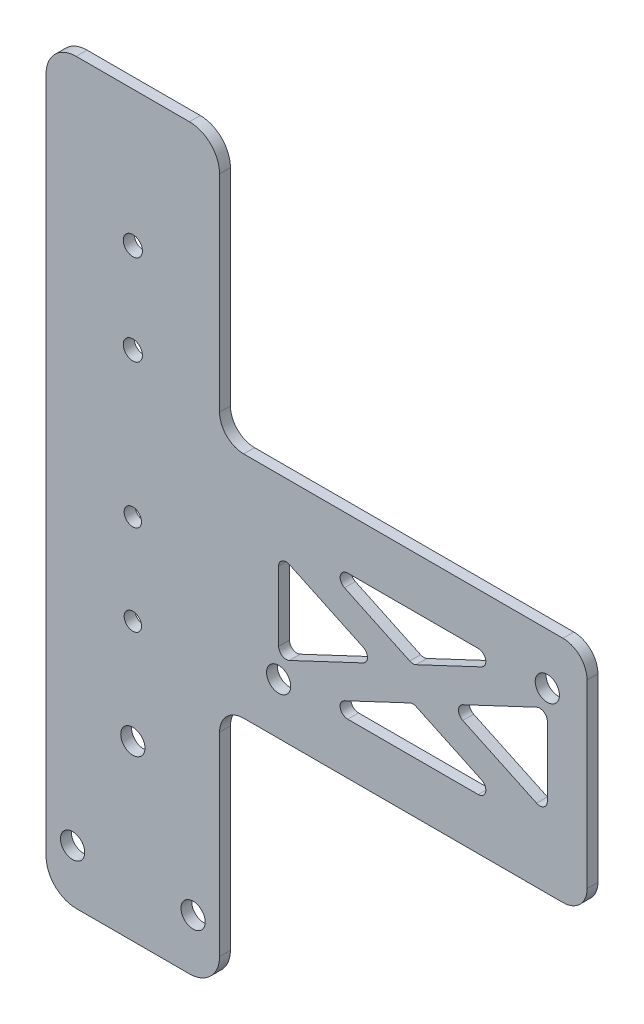
SolidWorks part; units mm, degrees
ref_plane "Front Plane" through (0, 0, 0) normal (0, 0, 1) x (1, 0, 0)
ref_plane "Top Plane" through (0, 0, 0) normal (0, 1, 0) x (1, 0, 0)
ref_plane "Right Plane" through (0, 0, 0) normal (1, 0, 0) x (0, 0, -1)
ref_plane "Plane1" through (0, 0, 1.5875) normal (0, 0, 1) x (1, 0, 0)
sketch "Sketch1" plane through (0, 0, 1.5875) normal (0, 0, 1) x (1, 0, 0)
  line L8 (18.288, -65.0875) -> (18.288, -24.13)
  line L9 (23.368, -19.05) -> (90.678, -19.05)
  line L10 (95.758, -13.97) -> (95.758, 24.13)
  line L11 (90.678, 29.21) -> (23.368, 29.21)
  line L12 (18.288, 34.29) -> (18.288, 77.7875)
  line L13 (11.938, 84.1375) -> (-11.938, 84.1375)
  line L14 (-18.288, 77.7875) -> (-18.288, -65.0875)
  line L15 (-11.938, -71.4375) -> (11.938, -71.4375)
  circle A8 centre (87.376, 18.415) radius 2.5527
  circle A9 centre (30.734, -8.255) radius 2.5527
  circle A12 centre (0, -13.0175) radius 1.8288
  circle A13 centre (0, 6.0325) radius 1.8288
  circle A14 centre (0, 36.5125) radius 2.0193
  circle A15 centre (0, 55.5625) radius 2.0193
  arc A16 (18.288, -24.13) -> (23.368, -19.05) centre (23.368, -24.13) cw
  arc A17 (90.678, -19.05) -> (95.758, -13.97) centre (90.678, -13.97) ccw
  arc A18 (95.758, 24.13) -> (90.678, 29.21) centre (90.678, 24.13) ccw
  arc A19 (23.368, 29.21) -> (18.288, 34.29) centre (23.368, 34.29) cw
  arc A20 (18.288, 77.7875) -> (11.938, 84.1375) centre (11.938, 77.7875) ccw
  arc A21 (-11.938, 84.1375) -> (-18.288, 77.7875) centre (-11.938, 77.7875) ccw
  arc A22 (-18.288, -65.0875) -> (-11.938, -71.4375) centre (-11.938, -65.0875) ccw
  arc A23 (11.938, -71.4375) -> (18.288, -65.0875) centre (11.938, -65.0875) ccw
  circle A40 centre (12.7, -60.325) radius 2.5527
  circle A41 centre (-12.7, -60.325) radius 2.5527
  circle A42 centre (0, -34.925) radius 2.5527
extrude "Boss-Extrude1" add sketch "Sketch1" against normal blind 2.286
sketch "Sketch2" plane through (0, 0, 1.5875) normal (0, 0, 1) x (1, 0, 0)
  line L0 (95.758, 5.08) -> (19.3492, 5.08) construction
  line L1 (30.734, 18.415) -> (87.376, 18.415)
  line L2 (30.734, 18.415) -> (30.734, -8.255)
  line L3 (30.734, -8.255) -> (87.376, -8.255)
  line L4 (87.376, 18.415) -> (87.376, -8.255)
  line L5 (30.734, 18.415) -> (87.376, -8.255) construction
  line L6 (30.734, -8.255) -> (87.376, 18.415) construction
  line L7 (95.758, -13.97) -> (95.758, 24.13) construction
  line L8 (33.909, 15.24) -> (84.201, 15.24) construction
  line L9 (84.201, 15.24) -> (84.201, -5.08) construction
  line L10 (33.909, -5.08) -> (84.201, -5.08) construction
  line L11 (33.909, 15.24) -> (33.909, -5.08) construction
  line L12 (32.0865, -11.1275) -> (88.7285, 15.5425)
  line L13 (29.3815, 15.5425) -> (86.0235, -11.1275)
  line L14 (29.3815, -5.3825) -> (86.0235, 21.2875)
  line L15 (32.0865, 21.2875) -> (88.7285, -5.3825)
  line L17 (24.13, 27.305) -> (93.98, 27.305)
  line L18 (24.13, 27.305) -> (24.13, -17.145)
  line L19 (24.13, -17.145) -> (93.98, -17.145)
  line L20 (93.98, 27.305) -> (93.98, -17.145)
  line L21 (24.13, 27.305) -> (93.98, -17.145) construction
  line L22 (24.13, -17.145) -> (93.98, 27.305) construction
  point P0 (59.055, 5.08)
  point P9 (30.734, -8.255)
  point P10 (87.376, 18.415)
  point P25 (59.055, 5.08)
  dimension "D1" = 3.175
  dimension "D2" = 3.175
  dimension "D4" = 69.85
  dimension "D5" = 44.45
  dimension "D3" = 3.175
extrude "Cut-Extrude1" cut sketch "Sketch2" against normal through all contours L1 L15 L14 | L2 L14 L13 | L13 L12 L3 | L12 L15 L4
fillet "Fillet1" radius 1.5875 12 edges at (87.376, 14.9057, 0.4445) (87.376, -4.7457, 0.4445) (66.5082, 5.08, 0.4445) (79.9228, 18.415, 0.4445) (59.055, 8.5893, 0.4445) (38.1872, 18.415, 0.4445) (51.6018, 5.08, 0.4445) (30.734, 14.9057, 0.4445) (79.9228, -8.255, 0.4445) (38.1872, -8.255, 0.4445) (59.055, 1.5707, 0.4445) (30.734, -4.7457, 0.4445)
